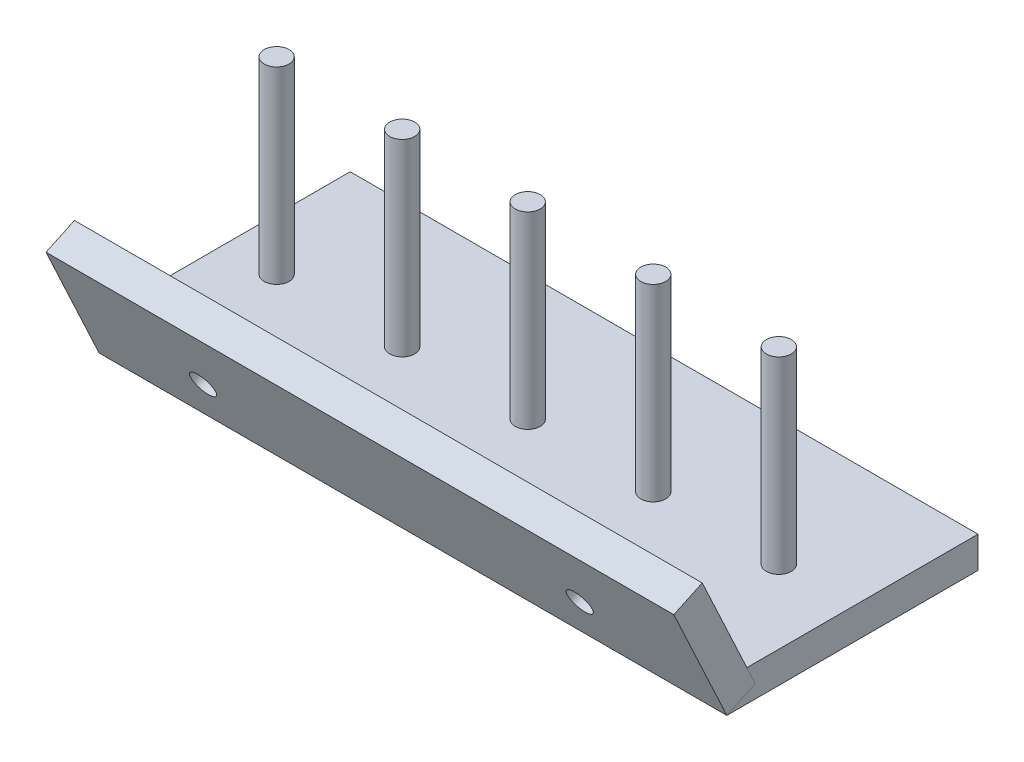
SolidWorks part; units mm, degrees
ref_plane "Front Plane" through (0, 0, 0) normal (0, 0, 1) x (1, 0, 0)
ref_plane "Top Plane" through (0, 0, 0) normal (0, 1, 0) x (1, 0, 0)
ref_plane "Right Plane" through (0, 0, 0) normal (1, 0, 0) x (0, 0, -1)
sketch "Esquisse1" plane through (0, 0, 0) normal (0, 1, 0) x (1, 0, 0)
  line L1 (-50, 20) -> (50, 20)
  line L2 (-50, 20) -> (-50, -20)
  line L3 (-50, -20) -> (50, -20)
  line L4 (50, 20) -> (50, -20)
  point P4 (0, 20)
  point P6 (-50, 0)
  dimension "D1" = 40
  dimension "D2" = 100
extrude "Boss.-Extru.1" add sketch "Esquisse1" along normal blind 5
ref_plane "Plan1" through (0, -7.6604, 16.4279) normal (0, -0.4226, 0.9063) x (1, 0, 0)
sketch "Esquisse3" plane through (0, -7.6604, 16.4279) normal (0, -0.4226, 0.9063) x (1, 0, 0)
  line L1 (-50, 8.4524) -> (50, 8.4524)
  line L2 (-50, 8.4524) -> (-50, 28.4524)
  line L3 (-50, 28.4524) -> (50, 28.4524)
  line L4 (50, 8.4524) -> (50, 28.4524)
  dimension "D1" = 20
extrude "Boss.-Extru.2" add sketch "Esquisse3" against normal blind 5 separate body
sketch "Esquisse4" plane through (0, 5, 0) normal (0, 1, 0) x (1, 0, 0)
  line L0 (-50, 0) -> (50, 0) construction
  line L1 (-50, 20) -> (-50, -20) construction
  line L2 (50, -20) -> (50, 20) construction
  circle A0 centre (38.2805, 0) radius 1.9892
  circle A1 centre (18.2805, 0) radius 1.9892
  circle A2 centre (-1.7195, 0) radius 1.9892
  circle A3 centre (-21.7195, 0) radius 1.9892
  circle A4 centre (-41.7195, 0) radius 1.9892
  dimension "D1" = 5
extrude "Boss.-Extru.3" add sketch "Esquisse4" along normal blind 30
sketch "Esquisse5" plane through (0, -7.6604, 16.4279) normal (0, -0.4226, 0.9063) x (1, 0, 0)
  line L0 (-50, 28.4524) -> (-50, 8.4524) construction
  line L1 (50, 8.4524) -> (50, 28.4524) construction
  circle A0 centre (-30, 16.5961) radius 2
  circle A1 centre (30, 16.5961) radius 2
  point P4 (-31.6293, 16.3901)
  point P5 (-30.2602, 16.5961)
  point P6 (30.3225, 16.5961)
  dimension "D1" = 20
  dimension "D2" = 20
extrude "Enlèv. mat.-Extru.1" cut sketch "Esquisse5" against normal blind 10
sketch "Esquisse6" plane through (0, -5.5474, 11.8963) normal (0, 0.4226, -0.9063) x (-1, 0, 0)
  circle A0 centre (-30, 16.5961) radius 2.9956
  circle A1 centre (30, 16.5961) radius 3
extrude "Enlèv. mat.-Extru.2" cut sketch "Esquisse6" against normal blind 2 and the other way through all
